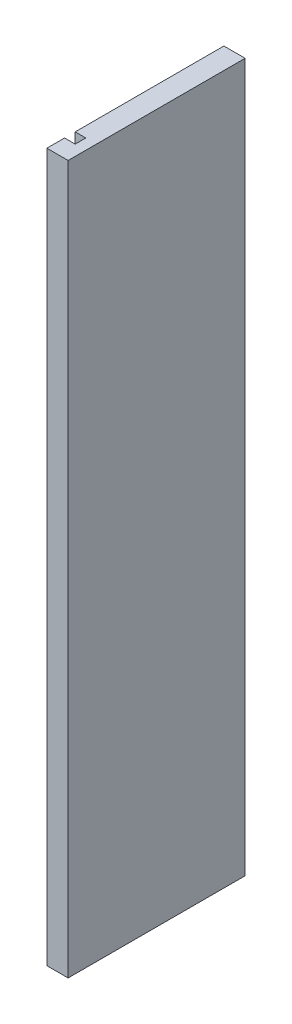
SolidWorks part; units mm, degrees
ref_plane "Alzado" through (0, 0, 0) normal (0, 0, 1) x (1, 0, 0)
ref_plane "Planta" through (0, 0, 0) normal (0, 1, 0) x (1, 0, 0)
ref_plane "Vista lateral" through (0, 0, 0) normal (1, 0, 0) x (0, 0, -1)
sketch "Croquis1" plane through (0, 0, 0) normal (0, 1, 0) x (1, 0, 0)
  line L0 (12, 24.2448) -> (12, -75.7552)
  line L1 (12, -75.7552) -> (0, -75.7552)
  line L2 (0, -75.7552) -> (0, -65.7552)
  line L3 (0, -65.7552) -> (6, -65.7552)
  line L4 (6, -65.7552) -> (6, -59.7552)
  line L5 (6, -59.7552) -> (0, -59.7552)
  line L6 (0, -59.7552) -> (0, 24.2448)
  line L7 (0, 24.2448) -> (12, 24.2448)
  point P2 (0, 0)
  dimension "D1" = 12
  dimension "D2" = 12
  dimension "D3" = 6
  dimension "D4" = 6
  dimension "D5" = 10
  dimension "D6" = 100
extrude "Saliente-Extruir2" add sketch "Croquis1" along normal blind 400
